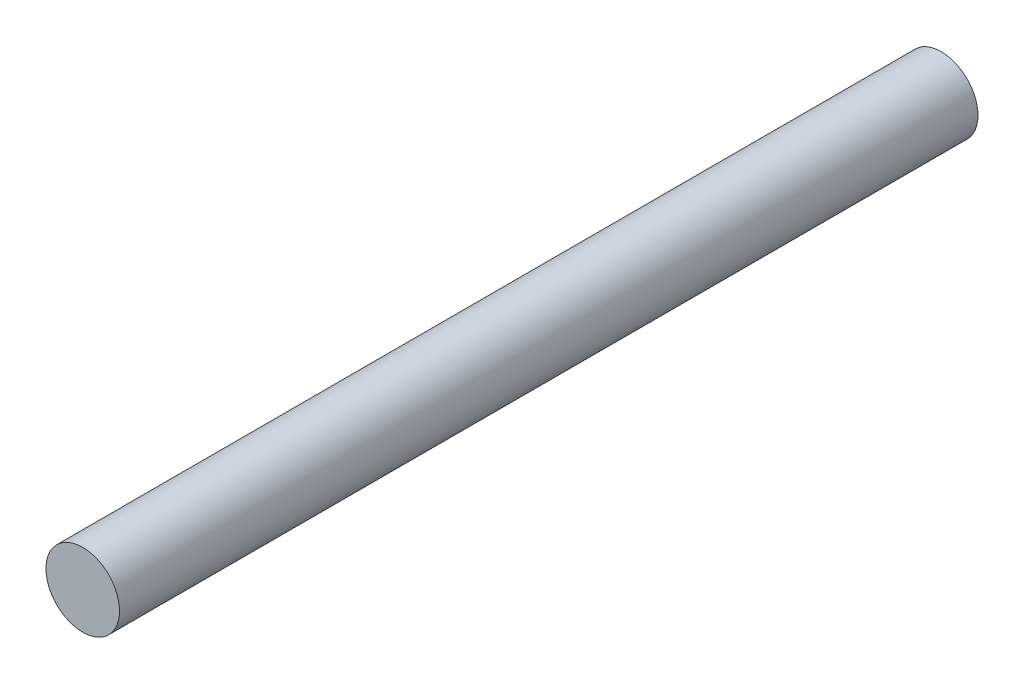
SolidWorks part; units mm, degrees
ref_plane "前视基准面" through (0, 0, 0) normal (0, 0, 1) x (1, 0, 0)
ref_plane "上视基准面" through (0, 0, 0) normal (0, 1, 0) x (1, 0, 0)
ref_plane "右视基准面" through (0, 0, 0) normal (1, 0, 0) x (0, 0, -1)
sketch "草图1" plane through (0, 0, 0) normal (0, 0, 1) x (1, 0, 0)
  circle A0 centre (0, 0) radius 3
extrude "凸台-拉伸1" add sketch "草图1" along normal blind 70
